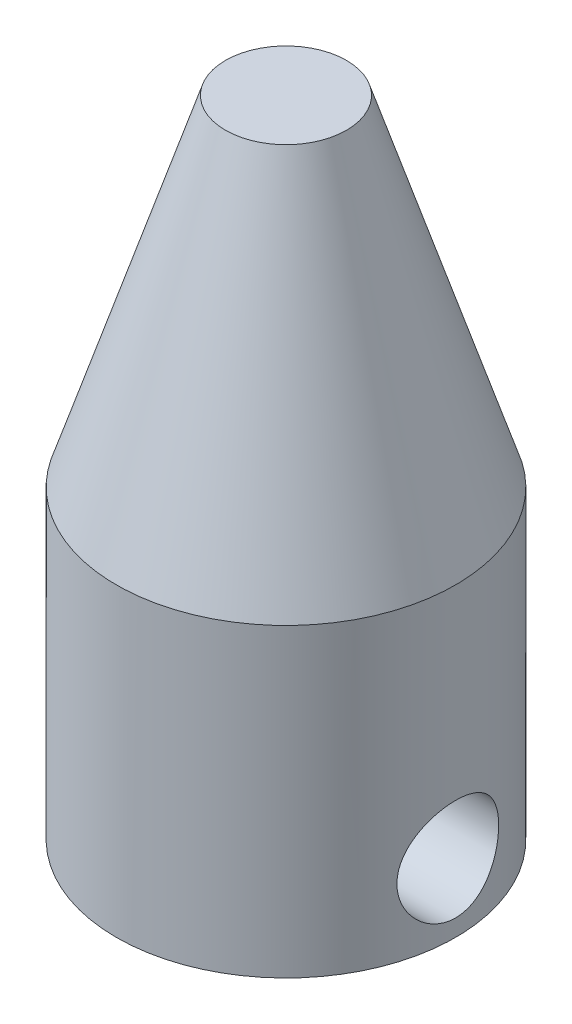
SolidWorks part; units mm, degrees
ref_plane "Front Plane" through (0, 0, 0) normal (0, 0, 1) x (1, 0, 0)
ref_plane "Top Plane" through (0, 0, 0) normal (0, 1, 0) x (1, 0, 0)
ref_plane "Right Plane" through (0, 0, 0) normal (1, 0, 0) x (0, 0, -1)
sketch "Sketch1" plane through (0, 0, 0) normal (0, 1, 0) x (1, 0, 0)
  circle A0 centre (0, 0) radius 5
  dimension "D1" = 10
extrude "body" add sketch "Sketch1" along normal blind 9
sketch "Sketch2" plane through (0, 0, 0) normal (1, 0, 0) x (0, 0, -1)
  circle A0 centre (0, 2) radius 1.5
  dimension "D1" = 2
  dimension "D2" = 3
extrude "pin insert" cut sketch "Sketch2" against normal through all and the other way through all
ref_plane "contact plane" through (0, 19, 0) normal (0, 1, 0) x (1, 0, 0)
sketch "head SA" plane through (0, 19, 0) normal (0, 1, 0) x (1, 0, 0)
  circle A0 centre (0, 0) radius 1.784
  dimension "D1" = 3.568
loft "cone" add profiles "head SA" section "head SA" section face at (0, 9, 5)
